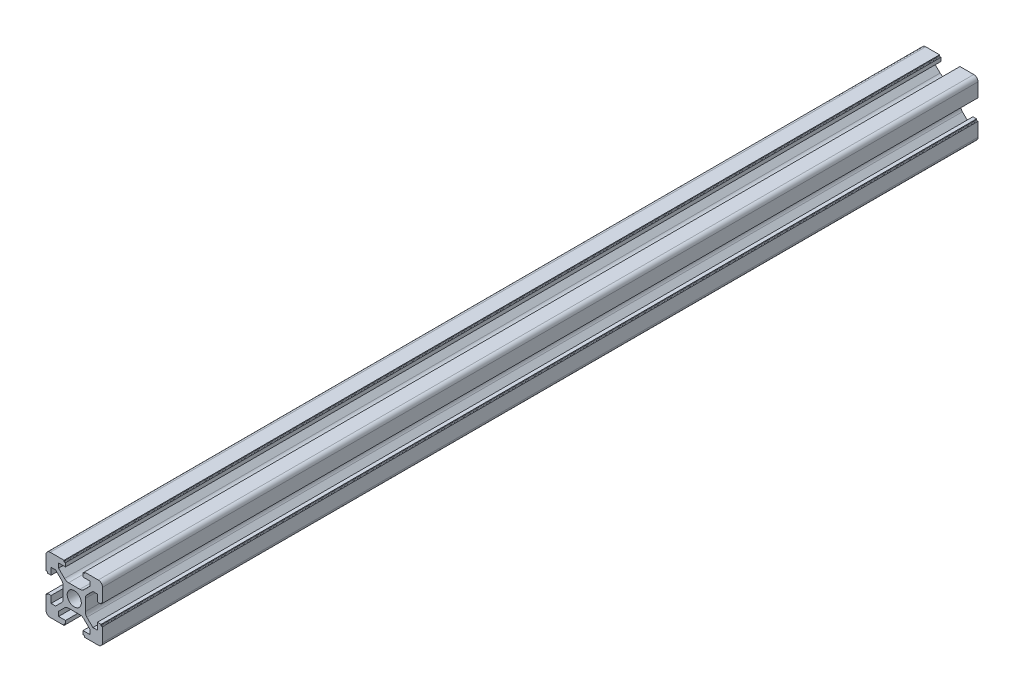
SolidWorks part; units mm, degrees
ref_plane "Спереди" through (0, 0, 0) normal (0, 0, 1) x (1, 0, 0)
ref_plane "Сверху" through (0, 0, 0) normal (0, 1, 0) x (1, 0, 0)
ref_plane "Справа" through (0, 0, 0) normal (1, 0, 0) x (0, 0, -1)
sketch "Sketch1" plane through (0, 0, 0) normal (0, 0, 1) x (1, 0, 0)
  line L0 (0, 10) -> (0, -10) construction
  line L1 (-10, -10) -> (10, -10) construction
  line L2 (-10, -10) -> (-10, 10) construction
  line L3 (-10, 10) -> (10, 10) construction
  line L4 (10, -10) -> (10, 10) construction
  line L5 (-10, -10) -> (10, 10) construction
  line L6 (-10, 10) -> (10, -10) construction
  line L7 (-10, 0) -> (10, 0) construction
  line L8 (0, 3.9) -> (-2.0109, 3.9)
  line L9 (-3.4251, 4.4858) -> (-5.5393, 6.6)
  line L10 (-5.5393, 6.6) -> (-5.5393, 8.2)
  line L11 (-5.5393, 8.2) -> (-3.1, 8.2)
  line L12 (-3.1, 8.2) -> (-3.1, 9.5)
  line L13 (-3.1, 9.5) -> (-3.4, 9.5)
  line L14 (-3.6, 9.7) -> (-3.6, 10)
  line L15 (-3.6, 10) -> (-8.5, 10)
  line L16 (-10, 3.6) -> (-10, 8.5)
  line L17 (-9.7, 3.6) -> (-10, 3.6)
  line L18 (-9.5, 3.1) -> (-9.5, 3.4)
  line L19 (-8.2, 3.1) -> (-9.5, 3.1)
  line L20 (-8.2, 5.5393) -> (-8.2, 3.1)
  line L21 (-6.6, 5.5393) -> (-8.2, 5.5393)
  line L22 (-4.4858, 3.4251) -> (-6.6, 5.5393)
  line L23 (-3.9, 0) -> (-3.9, 2.0109)
  line L24 (3.9, 0) -> (3.9, 2.0109)
  line L25 (4.4858, 3.4251) -> (6.6, 5.5393)
  line L26 (6.6, 5.5393) -> (8.2, 5.5393)
  line L27 (8.2, 5.5393) -> (8.2, 3.1)
  line L28 (8.2, 3.1) -> (9.5, 3.1)
  line L29 (9.5, 3.1) -> (9.5, 3.4)
  line L30 (9.7, 3.6) -> (10, 3.6)
  line L31 (10, 3.6) -> (10, 8.5)
  line L32 (3.6, 10) -> (8.5, 10)
  line L33 (3.6, 9.7) -> (3.6, 10)
  line L34 (3.1, 9.5) -> (3.4, 9.5)
  line L35 (3.1, 8.2) -> (3.1, 9.5)
  line L36 (5.5393, 8.2) -> (3.1, 8.2)
  line L37 (5.5393, 6.6) -> (5.5393, 8.2)
  line L38 (3.4251, 4.4858) -> (5.5393, 6.6)
  line L39 (0, 3.9) -> (2.0109, 3.9)
  line L40 (0, -3.9) -> (2.0109, -3.9)
  line L41 (3.4251, -4.4858) -> (5.5393, -6.6)
  line L42 (5.5393, -6.6) -> (5.5393, -8.2)
  line L43 (5.5393, -8.2) -> (3.1, -8.2)
  line L44 (3.1, -8.2) -> (3.1, -9.5)
  line L45 (3.1, -9.5) -> (3.4, -9.5)
  line L46 (3.6, -9.7) -> (3.6, -10)
  line L47 (3.6, -10) -> (8.5, -10)
  line L48 (10, -3.6) -> (10, -8.5)
  line L49 (9.7, -3.6) -> (10, -3.6)
  line L50 (9.5, -3.1) -> (9.5, -3.4)
  line L51 (8.2, -3.1) -> (9.5, -3.1)
  line L52 (8.2, -5.5393) -> (8.2, -3.1)
  line L53 (6.6, -5.5393) -> (8.2, -5.5393)
  line L54 (4.4858, -3.4251) -> (6.6, -5.5393)
  line L55 (3.9, 0) -> (3.9, -2.0109)
  line L56 (-3.9, 0) -> (-3.9, -2.0109)
  line L57 (-4.4858, -3.4251) -> (-6.6, -5.5393)
  line L58 (-6.6, -5.5393) -> (-8.2, -5.5393)
  line L59 (-8.2, -5.5393) -> (-8.2, -3.1)
  line L60 (-8.2, -3.1) -> (-9.5, -3.1)
  line L61 (-9.5, -3.1) -> (-9.5, -3.4)
  line L62 (-9.7, -3.6) -> (-10, -3.6)
  line L63 (-10, -3.6) -> (-10, -8.5)
  line L64 (-3.6, -10) -> (-8.5, -10)
  line L65 (-3.6, -9.7) -> (-3.6, -10)
  line L66 (-3.1, -9.5) -> (-3.4, -9.5)
  line L67 (-3.1, -8.2) -> (-3.1, -9.5)
  line L68 (-5.5393, -8.2) -> (-3.1, -8.2)
  line L69 (-5.5393, -6.6) -> (-5.5393, -8.2)
  line L70 (-3.4251, -4.4858) -> (-5.5393, -6.6)
  line L71 (0, -3.9) -> (-2.0109, -3.9)
  circle A0 centre (0, 0) radius 2.5
  arc A1 (-8.5, 10) -> (-10, 8.5) centre (-8.5, 8.5) ccw
  arc A2 (-2.0109, 3.9) -> (-3.4251, 4.4858) centre (-2.0109, 5.9) cw
  arc A3 (-3.4, 9.5) -> (-3.6, 9.7) centre (-3.4, 9.7) cw
  arc A4 (-9.5, 3.4) -> (-9.7, 3.6) centre (-9.7, 3.4) ccw
  arc A5 (-3.9, 2.0109) -> (-4.4858, 3.4251) centre (-5.9, 2.0109) ccw
  arc A6 (10, 8.5) -> (8.5, 10) centre (8.5, 8.5) ccw
  arc A7 (3.9, 2.0109) -> (4.4858, 3.4251) centre (5.9, 2.0109) cw
  arc A8 (9.5, 3.4) -> (9.7, 3.6) centre (9.7, 3.4) cw
  arc A9 (3.4, 9.5) -> (3.6, 9.7) centre (3.4, 9.7) ccw
  arc A10 (2.0109, 3.9) -> (3.4251, 4.4858) centre (2.0109, 5.9) ccw
  arc A11 (8.5, -10) -> (10, -8.5) centre (8.5, -8.5) ccw
  arc A12 (2.0109, -3.9) -> (3.4251, -4.4858) centre (2.0109, -5.9) cw
  arc A13 (3.4, -9.5) -> (3.6, -9.7) centre (3.4, -9.7) cw
  arc A14 (9.5, -3.4) -> (9.7, -3.6) centre (9.7, -3.4) ccw
  arc A15 (3.9, -2.0109) -> (4.4858, -3.4251) centre (5.9, -2.0109) ccw
  arc A16 (-10, -8.5) -> (-8.5, -10) centre (-8.5, -8.5) ccw
  arc A17 (-3.9, -2.0109) -> (-4.4858, -3.4251) centre (-5.9, -2.0109) cw
  arc A18 (-9.5, -3.4) -> (-9.7, -3.6) centre (-9.7, -3.4) cw
  arc A19 (-3.4, -9.5) -> (-3.6, -9.7) centre (-3.4, -9.7) ccw
  arc A20 (-2.0109, -3.9) -> (-3.4251, -4.4858) centre (-2.0109, -5.9) ccw
  point P0 (0, 0)
  point P42 (0, 0)
  point P70 (0, 0)
  point P98 (0, 0)
  point P126 (0, 0)
  dimension "D3" = 5
  dimension "D4" = 3
  dimension "D12" = 2
  dimension "D13" = 0.2
  dimension "D1" = 20
  dimension "D2" = 20
  dimension "D5" = 6.2
  dimension "D6" = 7.2
  dimension "D7" = 1.8
  dimension "D8" = 0.5
  dimension "D9" = 3.4
  dimension "D10" = 1.5
  dimension "D11" = 6.1
  dimension "D14" = 4
extrude "Бобышка-Вытянуть1" add sketch "Sketch1" along normal blind 310
